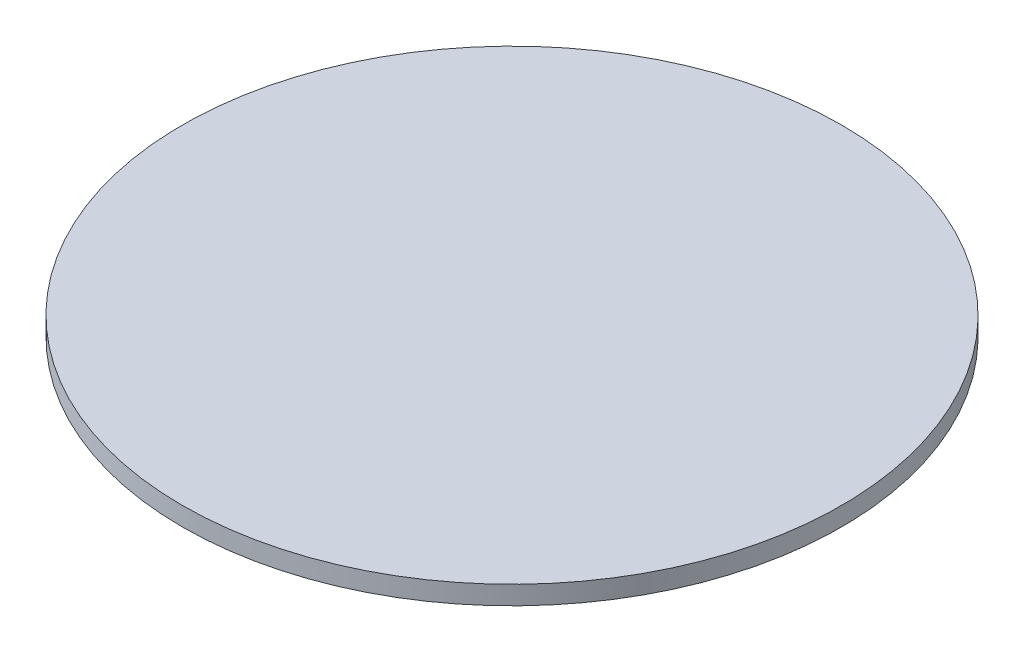
SolidWorks part; units mm, degrees
ref_plane "Front Plane" through (0, 0, 0) normal (0, 0, 1) x (1, 0, 0)
ref_plane "Top Plane" through (0, 0, 0) normal (0, 1, 0) x (1, 0, 0)
ref_plane "Right Plane" through (0, 0, 0) normal (1, 0, 0) x (0, 0, -1)
sketch "Sketch1" plane through (0, 0, 0) normal (0, 1, 0) x (1, 0, 0)
  circle A0 centre (0, 0) radius 3
  point P0 (0, 0)
  dimension "D3" = 6
extrude "Boss-Extrude1" add sketch "Sketch1" along normal blind 0.17
